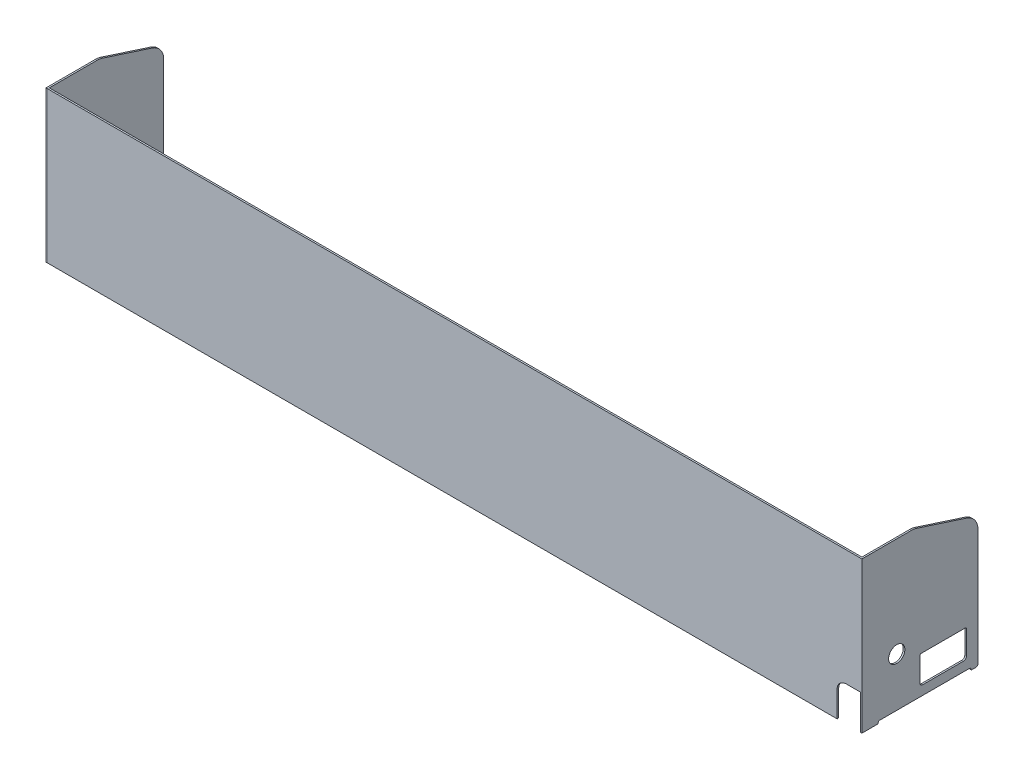
SolidWorks part; units mm, degrees
ref_plane "Front Plane" through (0, 0, 0) normal (0, 0, 1) x (1, 0, 0)
ref_plane "Top Plane" through (0, 0, 0) normal (0, 1, 0) x (1, 0, 0)
ref_plane "Right Plane" through (0, 0, 0) normal (1, 0, 0) x (0, 0, -1)
sketch "Sketch1" plane through (0, 0, 0) normal (0, 0, 1) x (1, 0, 0)
  line L0 (0, 283.3898) -> (0, -294.2373) construction
  line L1 (-518.8701, 0) -> (517.0621, 0) construction
  line L2 (175, -17.5) -> (169, -17.5)
  line L3 (-175, 32.5) -> (175, 32.5)
  line L4 (-175, 32.5) -> (-175, -32.5)
  line L5 (-175, -32.5) -> (165, -32.5)
  line L6 (175, 32.5) -> (175, -17.5)
  line L7 (165, -21.5) -> (165, -32.5)
  arc A0 (169, -17.5) -> (165, -21.5) centre (169, -21.5) ccw
  point P13 (165, -17.5)
  dimension "D5" = 4
  dimension "D1" = 350
  dimension "D2" = 65
  dimension "D3" = 10
  dimension "D4" = 15
extrude "Back Wall" add sketch "Sketch1" along normal blind 0.7
ref_plane "Right_wall Plane" through (-175, 0, 0) normal (-1, 0, 0) x (0, 0, 1)
sketch "Sketch2" plane through (-175, 0, 0) normal (-1, 0, 0) x (0, 0, 1)
  line L0 (-62.6179, 0) -> (70.933, 0) construction
  line L1 (0, 60.0387) -> (0, -42.0887) construction
  line L2 (-48.3, -32.5) -> (-46.5, -32.5)
  line L3 (-49.3, -31.5) -> (-49.3, 18.5)
  line L4 (0.7, 32.5) -> (0.7, -32.5) construction
  line L5 (0.7, 32.5) -> (-20.6433, 32.5)
  line L6 (0.7, 32.5) -> (0.7, -32.5)
  line L7 (-44.4529, 25.1607) -> (-22.7963, 32.1607)
  line L8 (-46.3, -32.3) -> (-46.3, -32.2)
  line L9 (-45.6, -31.5) -> (-7, -31.5)
  line L10 (-6.3, -32.2) -> (-6.3, -32.3)
  line L11 (-6.1, -32.5) -> (0.7, -32.5)
  line L13 (-43.8, -15.5) -> (-24.8, -15.5)
  line L14 (-44.3, -16) -> (-44.3, -26.3)
  line L15 (-43.1, -27.5) -> (-25.5, -27.5)
  line L16 (-24.3, -16) -> (-24.3, -26.3)
  arc A0 (-44.4529, 25.1607) -> (-49.3, 18.5) centre (-42.3, 18.5) ccw
  arc A1 (-20.6433, 32.5) -> (-22.7963, 32.1607) centre (-20.6433, 25.5) ccw
  arc A2 (-48.3, -32.5) -> (-49.3, -31.5) centre (-48.3, -31.5) cw
  arc A3 (-24.8, -15.5) -> (-24.3, -16) centre (-24.8, -16) cw
  arc A4 (-43.8, -15.5) -> (-44.3, -16) centre (-43.8, -16) ccw
  arc A5 (-24.3, -26.3) -> (-25.5, -27.5) centre (-25.5, -26.3) cw
  arc A6 (-43.1, -27.5) -> (-44.3, -26.3) centre (-43.1, -26.3) cw
  arc A7 (-45.6, -31.5) -> (-46.3, -32.2) centre (-45.6, -32.2) ccw
  arc A8 (-46.3, -32.3) -> (-46.5, -32.5) centre (-46.5, -32.3) cw
  arc A9 (-6.1, -32.5) -> (-6.3, -32.3) centre (-6.1, -32.3) cw
  arc A10 (-7, -31.5) -> (-6.3, -32.2) centre (-7, -32.2) cw
  circle A11 centre (-14.3, -10.5) radius 3.5
  point P16 (-49.3, 23.594)
  point P19 (-21.7465, 32.5)
  point P22 (-39.5789, -38.1792)
  point P43 (-46.3, -32.5)
  dimension "D4" = 7
  dimension "D5" = 7
  dimension "D6" = 1
  dimension "D16" = 0.5
  dimension "D17" = 1.2
  dimension "D18" = 0.7
  dimension "D19" = 0.2
  dimension "D20" = 0.2
  dimension "D21" = 0.7
  dimension "D22" = 7
  dimension "D1" = 50
  dimension "D3" = 50
  dimension "D7" = 3
  dimension "D8" = 1
  dimension "D9" = 7
  dimension "D10" = 2
  dimension "D11" = 22.7599
  dimension "D12" = 2
  dimension "D13" = 4
  dimension "D14" = 20
  dimension "D15" = 12
  dimension "D23" = 10
  dimension "0.5cm" = 5
extrude "Right Wall" add sketch "Sketch2" along normal blind 0.7 separate body
ref_plane "Left_wall Plane" through (175, 0, 0) normal (1, 0, 0) x (0, 0, -1)
ref_plane "Mid Plane" through (0, 0, 0) normal (1, 0, 0) x (0, 0, -1)
mirror "Mirror8" about plane through (0, 0, 0) normal (1, 0, 0) of "Right Wall"
sketch "Sketch3" plane through (0, 0, 0) normal (1, 0, 0) x (0, 0, -1)
